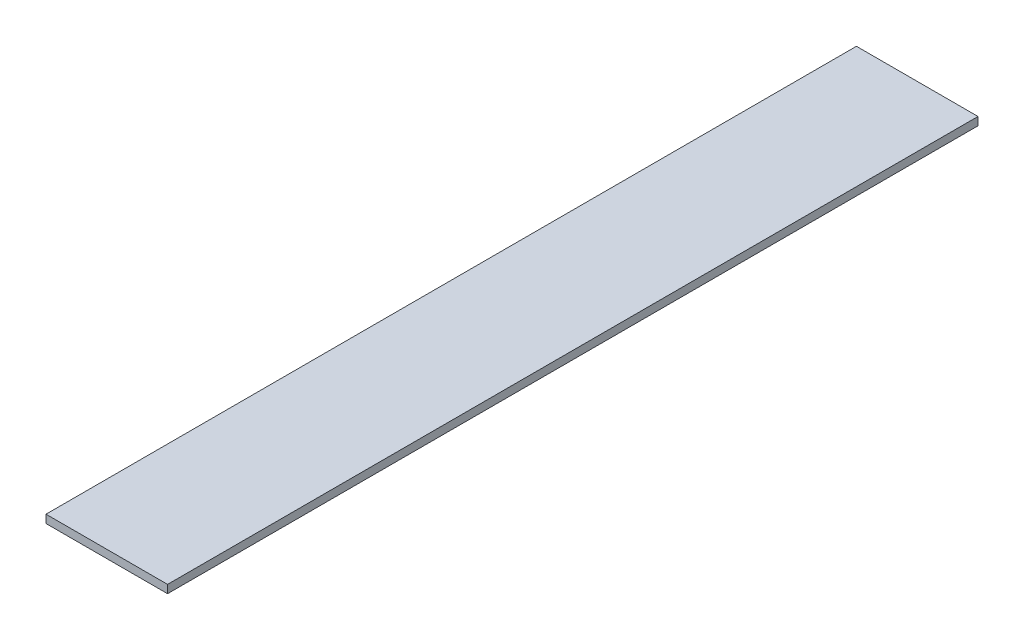
SolidWorks part; units mm, degrees
ref_plane "Front Plane" through (0, 0, 0) normal (0, 0, 1) x (1, 0, 0)
ref_plane "Top Plane" through (0, 0, 0) normal (0, 1, 0) x (1, 0, 0)
ref_plane "Right Plane" through (0, 0, 0) normal (1, 0, 0) x (0, 0, -1)
sketch "Sketch1" plane through (0, 0, 0) normal (0, 0, 1) x (1, 0, 0)
  line L1 (15, -1) -> (-15, -1)
  line L2 (15, -1) -> (15, 1)
  line L3 (15, 1) -> (-15, 1)
  line L4 (-15, -1) -> (-15, 1)
  line L5 (15, -1) -> (-15, 1) construction
  line L6 (15, 1) -> (-15, -1) construction
  point P0 (0, 0)
extrude "Boss-Extrude1" add sketch "Sketch1" along normal blind 200
